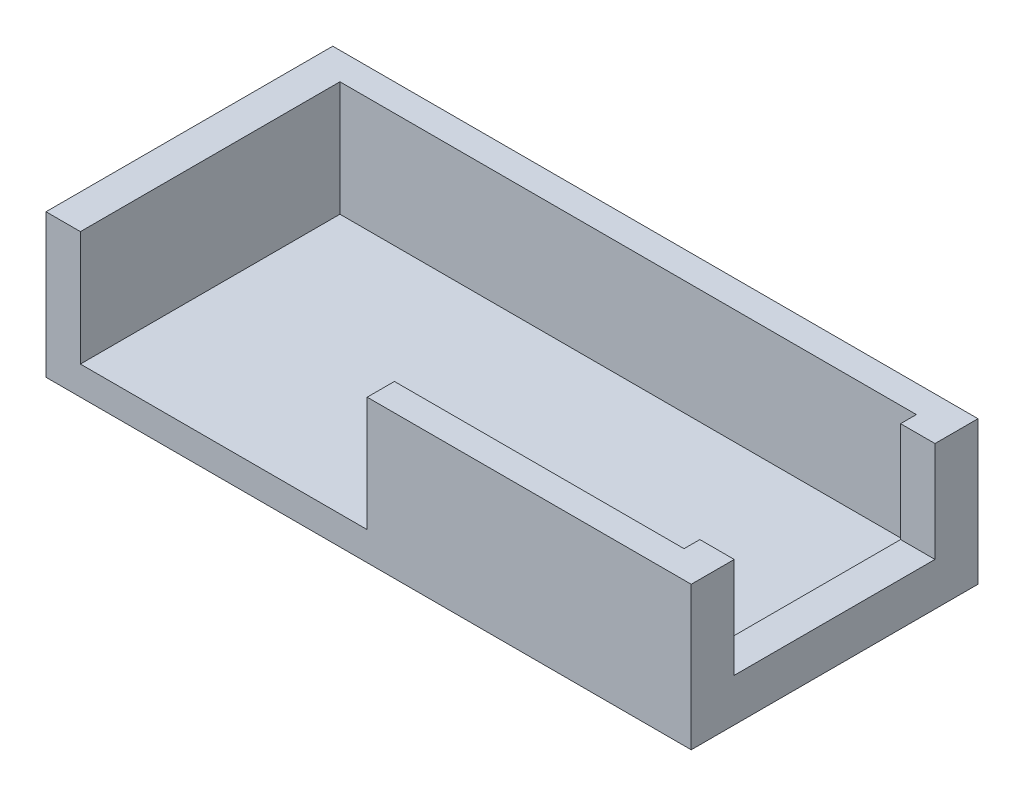
SolidWorks part; units mm, degrees
ref_plane "Alzado" through (0, 0, 0) normal (0, 0, 1) x (1, 0, 0)
ref_plane "Planta" through (0, 0, 0) normal (0, 1, 0) x (1, 0, 0)
ref_plane "Vista lateral" through (0, 0, 0) normal (1, 0, 0) x (0, 0, -1)
sketch "Croquis1" plane through (0, 0, 0) normal (0, 1, 0) x (1, 0, 0)
  line L1 (-22.5, -10) -> (22.5, -10)
  line L2 (-22.5, -10) -> (-22.5, 10)
  line L3 (-22.5, 10) -> (22.5, 10)
  line L4 (22.5, -10) -> (22.5, 10)
  line L5 (-22.5, -10) -> (22.5, 10) construction
  line L6 (-22.5, 10) -> (22.5, -10) construction
  point P0 (0, 0)
  dimension "D1" = 45
  dimension "D2" = 20
extrude "Saliente-Extruir1" add sketch "Croquis1" along normal blind 10
sketch "Croquis2" plane through (0, 10, 0) normal (0, 1, 0) x (1, 0, 0)
  line L1 (20.1, -8.1) -> (-20.1, -8.1)
  line L2 (20.1, -8.1) -> (20.1, 8.1)
  line L3 (20.1, 8.1) -> (-20.1, 8.1)
  line L4 (-20.1, -8.1) -> (-20.1, 8.1)
  line L5 (20.1, -8.1) -> (-20.1, 8.1) construction
  line L6 (20.1, 8.1) -> (-20.1, -8.1) construction
  point P0 (0, 0)
  dimension "D1" = 40.2
  dimension "D2" = 16.2
extrude "Cortar-Extruir1" cut sketch "Croquis2" against normal blind 8
sketch "Croquis3" plane through (22.5, 0, 0) normal (1, 0, 0) x (0, 0, -1)
  line L1 (-7, 10) -> (7, 10)
  line L2 (-7, 10) -> (-7, 3)
  line L3 (-7, 3) -> (7, 3)
  line L4 (7, 10) -> (7, 3)
  line L5 (-7, 10) -> (7, 3) construction
  line L6 (-7, 3) -> (7, 10) construction
  line L7 (-10, 10) -> (10, 10) construction
  line L8 (-10, 0) -> (10, 0) construction
  point P0 (0, 6.5)
  point P5 (0, 0)
  point P9 (7, 1.5867)
  dimension "D1" = 14
  dimension "D2" = 3
extrude "Cortar-Extruir2" cut sketch "Croquis3" against normal blind 8
sketch "Croquis4" plane through (0, 0, 10) normal (0, 0, 1) x (1, 0, 0)
  line L0 (-22.5, 0) -> (22.5, 0) construction
  line L1 (-20.1, 10) -> (-0.1, 10)
  line L2 (-20.1, 10) -> (-20.1, 2)
  line L3 (-20.1, 2) -> (-0.1, 2)
  line L4 (-0.1, 10) -> (-0.1, 2)
  dimension "D1" = 20
  dimension "D2" = 2
extrude "Cortar-Extruir3" cut sketch "Croquis4" against normal blind 8
